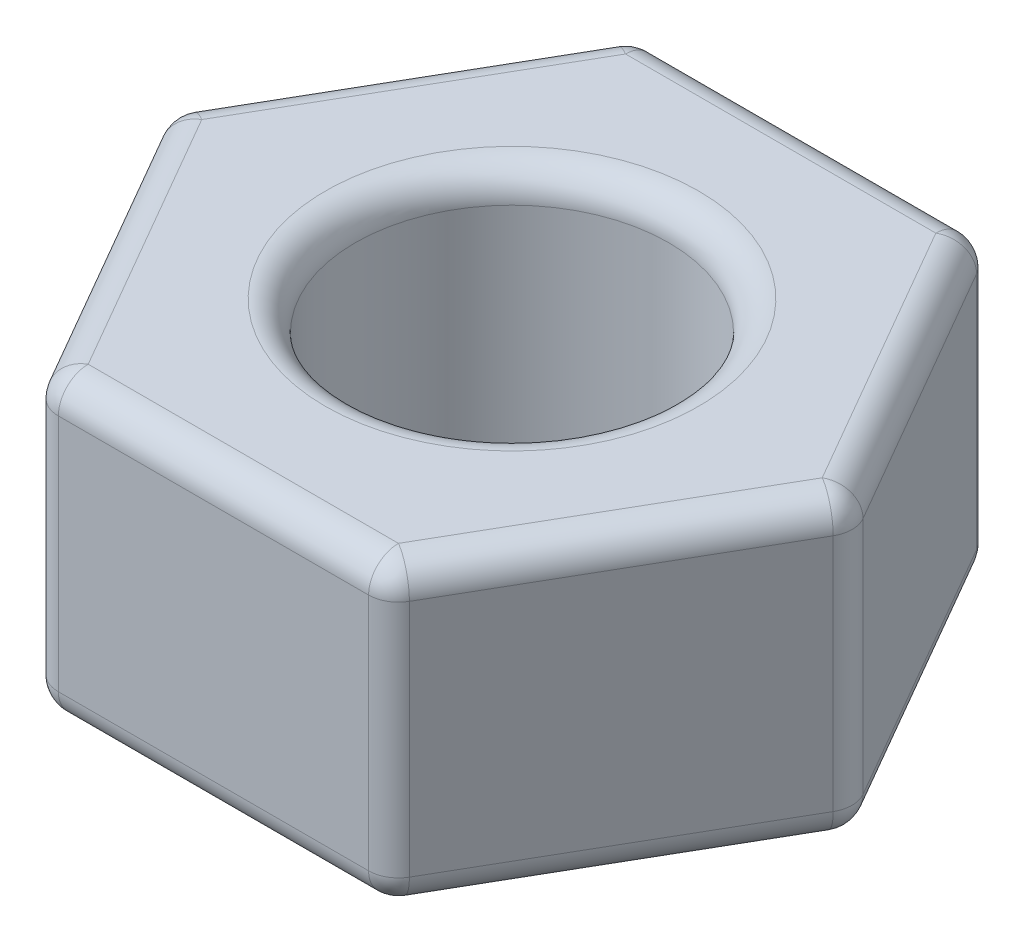
SolidWorks part; units mm, degrees
material "AISI 316 Stainless Steel Sheet (SS)"
ref_plane "Front Plane" through (0, 0, 0) normal (0, 0, 1) x (1, 0, 0)
ref_plane "Top Plane" through (0, 0, 0) normal (0, 1, 0) x (1, 0, 0)
ref_plane "Right Plane" through (0, 0, 0) normal (1, 0, 0) x (0, 0, -1)
sketch "Main Block Sketch" plane through (0, 0, 0) normal (0, 1, 0) x (1, 0, 0)
  line L1 (2.3094, 4) -> (-2.3094, 4)
  line L2 (-2.3094, 4) -> (-4.6188, 0)
  line L3 (-4.6188, 0) -> (-2.3094, -4)
  line L4 (-2.3094, -4) -> (2.3094, -4)
  line L5 (2.3094, -4) -> (4.6188, 0)
  line L6 (4.6188, 0) -> (2.3094, 4)
  circle A0 centre (0, 0) radius 4 construction
  dimension "D1" = 8
extrude "Main Block" add sketch "Main Block Sketch" along normal blind 4
hole_wizard "M5 Tapped section" positions "Sketch2" profile "Sketch3" tap size "M5" standard "ISO" end condition through all
sketch "Sketch2" plane through (0, 0, 0) normal (0, -1, 0) x (-1, 0, 0)
  point P0 (0, 0)
sketch "Sketch3" plane through (0, 0, 0) normal (1, 0, 0) x (0, 0, -1)
  line L0 (0, 0) -> (0, 4)
  line L1 (0, 4) -> (2.1, 4)
  line L2 (2.1, 4) -> (2.1, 0)
  line L5 (2.1, 0) -> (0, 0)
  line L11 (0, -6.35) -> (0, 107.95) construction
  dimension "Thru Tap Drill Dia." = 4.2
  dimension "Thru Tap Drill Depth" = 4
cosmetic thread "Hole Thread1" parameters "D2"=5
fillet "Cosmetic Fillets" radius 0.4 20 edges at (-2.3094, 2, 4) (-4.6188, 2, 0) (0, 4, 4) (-3.4641, 4, 2) (-3.4641, 4, -2) (0, 4, -4) (-2.3094, 2, -4) (3.4641, 4, -2) (2.3094, 2, -4) (2.3094, 2, 4) (3.4641, 4, 2) (4.6188, 2, 0) (0, 0, -4) (-3.4641, 0, -2) (-3.4641, 0, 2) (0, 0, 4) (3.4641, 0, 2) (3.4641, 0, -2) (0, 0, -2.1) (0, 4, -2.1)
